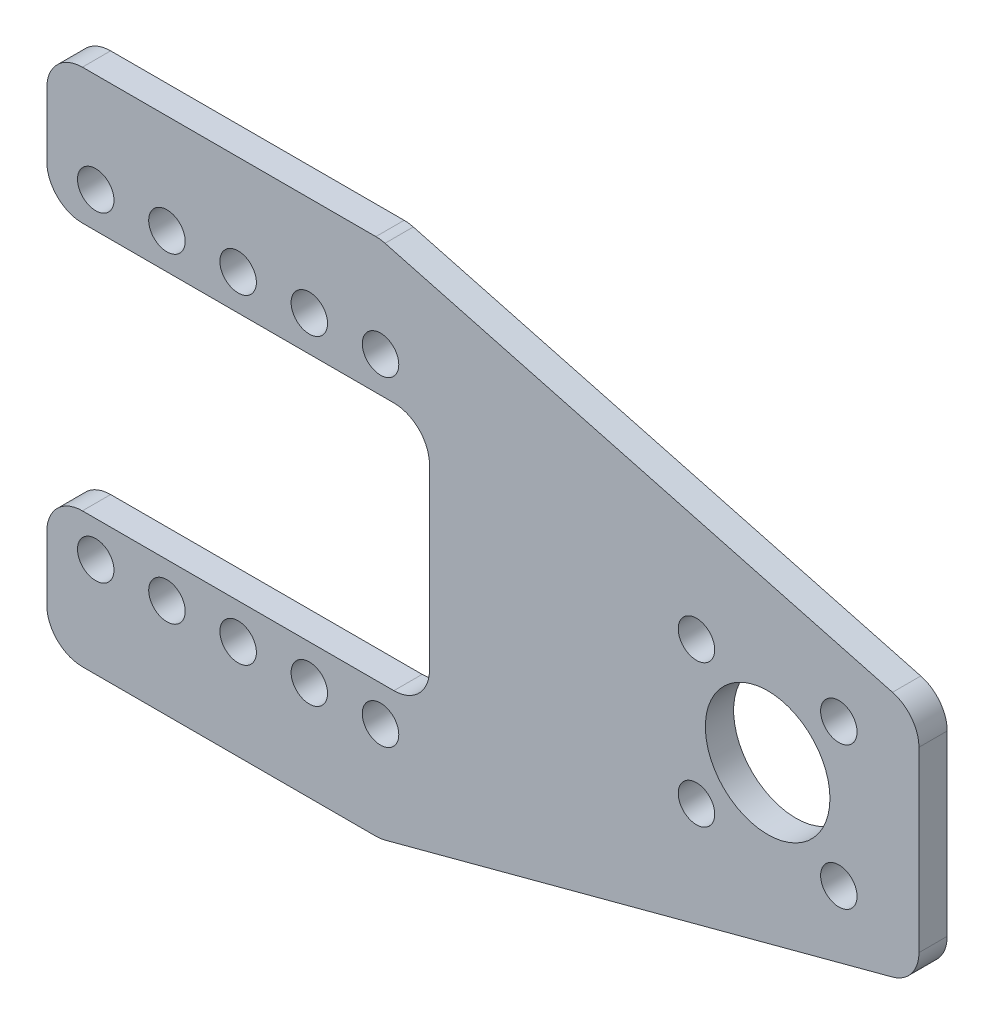
SolidWorks part; units mm, degrees
ref_plane "Front Plane" through (0, 0, 0) normal (0, 0, 1) x (1, 0, 0)
ref_plane "Top Plane" through (0, 0, 0) normal (0, 1, 0) x (1, 0, 0)
ref_plane "Right Plane" through (0, 0, 0) normal (1, 0, 0) x (0, 0, -1)
sketch "Sketch1" plane through (0, 0, 0) normal (0, 0, 1) x (1, 0, 0)
  line L0 (0, 0) -> (0, 15.175)
  line L1 (0, 15.175) -> (37.5, 15.175)
  line L4 (0, -43.175) -> (0, -28)
  line L5 (0, -28) -> (43, -28)
  line L6 (43, -28) -> (43, 0)
  line L7 (43, 0) -> (0, 0)
  line L8 (43, -14) -> (50043, -14) construction
  line L9 (81, -0.8217) -> (81, -50000.8217) construction
  line L10 (7.2742, 12) -> (50007.2742, 12) construction
  line L11 (73, -6) -> (89, -6) construction
  line L12 (73, -6) -> (73, -22) construction
  line L13 (73, -22) -> (89, -22) construction
  line L14 (89, -6) -> (89, -22) construction
  line L15 (73, -6) -> (89, -22) construction
  line L16 (73, -22) -> (89, -6) construction
  line L17 (6.3103, 4) -> (50006.3103, 4) construction
  line L18 (5.5, 9.521) -> (5.5, -49990.479) construction
  line L19 (5.5, 4) -> (13.5, 4) construction
  line L20 (98, -27.0658) -> (98, -0.9342) construction
  line L21 (37.5, 15.175) -> (98, -0.9342)
  line L22 (37.5, 4) -> (37.5, 50004) construction
  line L23 (158.5, 15.175) -> (98, -0.9342)
  line L24 (37.5, -43.175) -> (98, -27.0658)
  line L25 (98, -0.9342) -> (98, -27.0658)
  line L26 (37.5, -43.175) -> (0, -43.175)
  circle A0 centre (73, -6) radius 2.05
  circle A1 centre (89, -6) radius 2.05
  circle A2 centre (89, -22) radius 2.05
  circle A3 centre (73, -22) radius 2.05
  circle A4 centre (5.5, 4) radius 2.05
  circle A5 centre (13.5, 4) radius 2.05
  circle A6 centre (21.5, 4) radius 2.05
  circle A7 centre (29.5, 4) radius 2.05
  circle A8 centre (37.5, 4) radius 2.05
  circle A9 centre (37.5, -32) radius 2.05
  circle A10 centre (29.5, -32) radius 2.05
  circle A11 centre (21.5, -32) radius 2.05
  circle A12 centre (13.5, -32) radius 2.05
  circle A13 centre (5.5, -32) radius 2.05
  circle A14 centre (81, -14) radius 7
  circle A15 centre (81, -14) radius 17 construction
  point P12 (43, -14)
  point P14 (81, -14)
  point P61 (98, -14)
  dimension "D10" = 4.1
  dimension "D13" = 14
  dimension "D14" = 34
  dimension "D1" = 28
  dimension "D2" = 15.175
  dimension "D4" = 43
  dimension "D6" = 16
  dimension "D7" = 3.175
  dimension "D9" = 5.5
  dimension "D12" = 8
  dimension "D8" = 4
  dimension "D11" = 5
extrude "Boss-Extrude2" add sketch "Sketch1" along normal blind 3.175 contours L26 L24 L25 L21 L1 L0 L7 L6 L5 L4 A14 A12 A10 A0 A1 A2 A3 A4 A5 A6 A7 A8 A9 A11 A13
fillet "Fillet2" radius 4 10 edges at (0, 15.175, 1.5875) (37.5, 15.175, 1.5875) (43, -28, 1.5875) (43, 0, 1.5875) (0, 0, 1.5875) (0, -28, 1.5875) (0, -43.175, 1.5875) (37.5, -43.175, 1.5875) (98, -27.0658, 1.5875) (98, -0.9342, 1.5875)
equation "\"dbWidth\"= 43mm"
equation "\"mountWidth\"= 76mm"
equation "\"thick\"= 3.175mm"
equation "\"standoffHeight\"= 52mm"
equation "\"holeDistance\"= 32mm"
equation "\"sh\"= 4.1mm"
equation "\"dbHeight\"= 12mm"
equation "\"mountSq\"= 16mm"
equation "\"innerGap\"= 28mm"
equation "\"filet\"= 4mm"
equation "\"D1@Sketch1\"=\"innerGap\""
equation "\"D2@Sketch1\"=\"dbHeight\"+\"thick\""
equation "\"D4@Sketch1\"=\"dbWidth\""
equation "\"D6@Sketch1\"=\"mountSq\""
equation "\"D7@Sketch1\"=\"thick\""
equation "\"D10@Sketch1\"=\"sh\""
equation "\"D14@Sketch1\"=34"
equation "\"D1@Boss-Extrude2\"=\"thick\""
